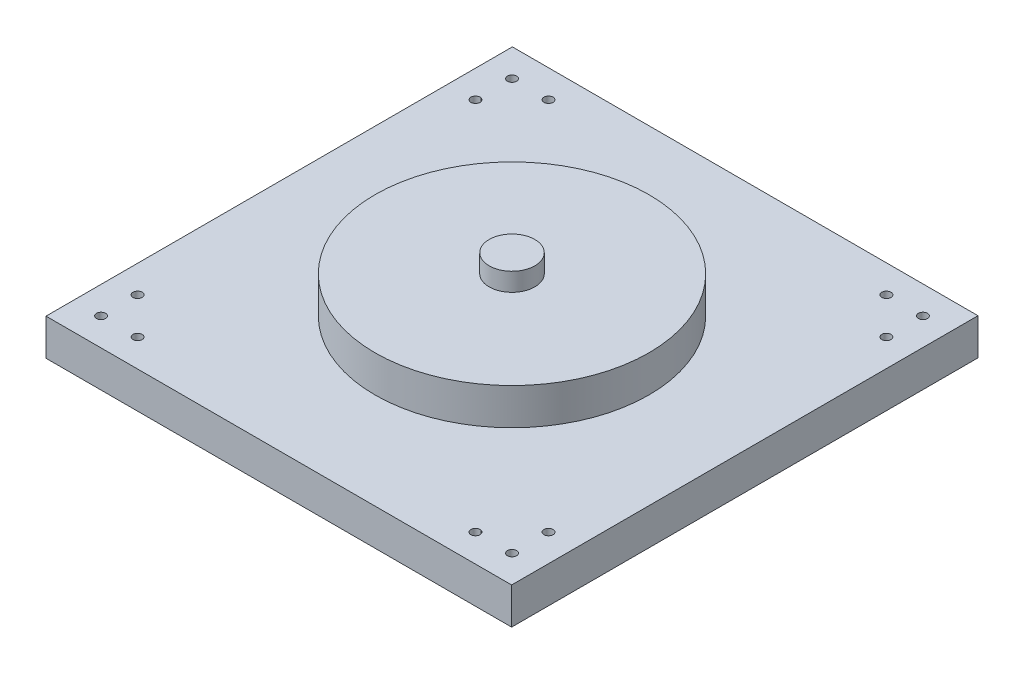
SolidWorks part; units mm, degrees
ref_plane "Front Plane" through (0, 0, 0) normal (0, 0, 1) x (1, 0, 0)
ref_plane "Top Plane" through (0, 0, 0) normal (0, 1, 0) x (1, 0, 0)
ref_plane "Right Plane" through (0, 0, 0) normal (1, 0, 0) x (0, 0, -1)
sketch "Sketch1" plane through (0, 0, 0) normal (0, 1, 0) x (1, 0, 0)
  line L1 (-32.3785, -32.4305) -> (32.3785, -32.4305)
  line L2 (-32.3785, -32.4305) -> (-32.3785, 32.4305)
  line L3 (-32.3785, 32.4305) -> (32.3785, 32.4305)
  line L4 (32.3785, -32.4305) -> (32.3785, 32.4305)
  line L5 (-32.3785, -32.4305) -> (32.3785, 32.4305) construction
  line L6 (-32.3785, 32.4305) -> (32.3785, -32.4305) construction
  circle A0 centre (-28.575, 28.575) radius 0.635
  circle A1 centre (-23.495, 28.575) radius 0.635
  circle A2 centre (-28.575, 23.495) radius 0.635
  circle A3 centre (28.575, 28.575) radius 0.635
  circle A4 centre (23.495, 28.575) radius 0.635
  circle A5 centre (28.575, 23.495) radius 0.635
  circle A6 centre (28.575, -28.575) radius 0.635
  circle A7 centre (28.575, -23.495) radius 0.635
  circle A8 centre (23.495, -28.575) radius 0.635
  circle A9 centre (-28.575, -28.575) radius 0.635
  circle A10 centre (-28.575, -23.495) radius 0.635
  circle A11 centre (-23.495, -28.575) radius 0.635
  point P0 (0, 0)
extrude "Boss-Extrude1" add sketch "Sketch1" along normal blind 5.08
sketch "Sketch2" plane through (0, 5.08, 0) normal (0, 1, 0) x (1, 0, 0)
  circle A0 centre (0, 0) radius 19.05
  dimension "D1" = 38.1
extrude "Boss-Extrude2" add sketch "Sketch2" along normal blind 5.08
sketch "Sketch3" plane through (0, 10.16, 0) normal (0, 1, 0) x (1, 0, 0)
  circle A0 centre (0, 0) radius 3.175
  dimension "D1" = 6.35
extrude "Boss-Extrude3" add sketch "Sketch3" along normal blind 2.54
